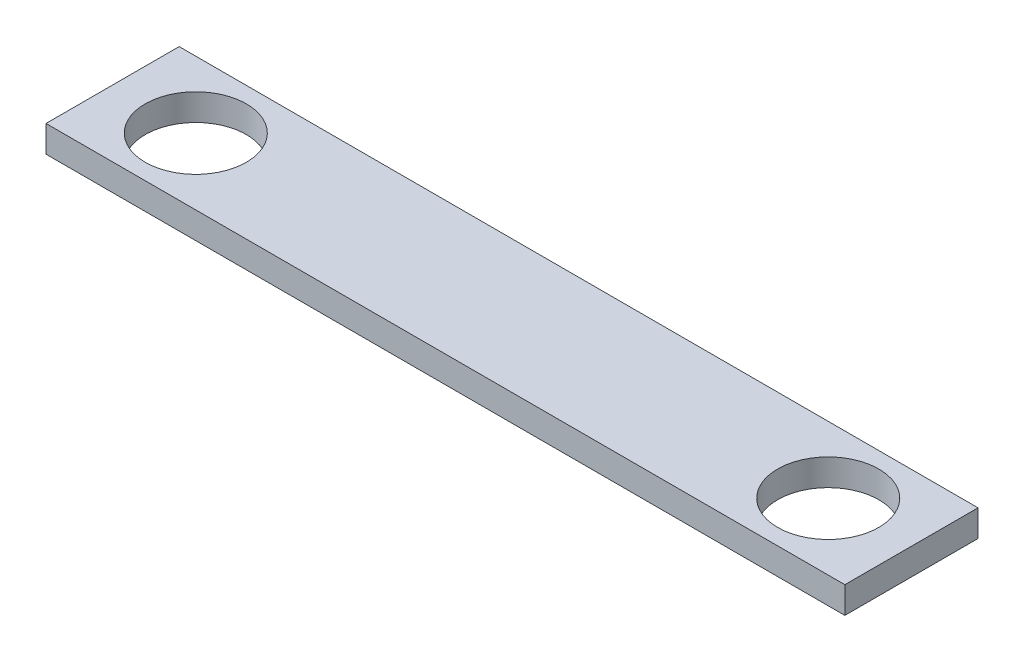
SolidWorks part; units mm, degrees
material "AISI 316 Annealed Stainless Steel Bar (SS)"
ref_plane "Front Plane" through (0, 0, 0) normal (0, 0, 1) x (1, 0, 0)
ref_plane "Top Plane" through (0, 0, 0) normal (0, 1, 0) x (1, 0, 0)
ref_plane "Right Plane" through (0, 0, 0) normal (1, 0, 0) x (0, 0, -1)
sketch "Sketch1" plane through (0, 0, 0) normal (0, 1, 0) x (1, 0, 0)
  line L0 (0, 6.35) -> (76.2, 6.35) construction
  line L1 (0, 0) -> (76.2, 0)
  line L2 (0, 0) -> (0, 12.7)
  line L3 (0, 12.7) -> (76.2, 12.7)
  line L4 (76.2, 0) -> (76.2, 12.7)
  line L5 (38.1, 12.7) -> (38.1, 0) construction
  circle A0 centre (7.9375, 6.35) radius 4.826
  circle A1 centre (68.2625, 6.35) radius 4.826
  dimension "D3" = 9.652
  dimension "D4" = 9.652
  dimension "D1" = 76.2
  dimension "D2" = 12.7
  dimension "D5" = 60.325
  dimension "D6" = 30.1625
extrude "Boss-Extrude1" add sketch "Sketch1" along normal blind 2.54
